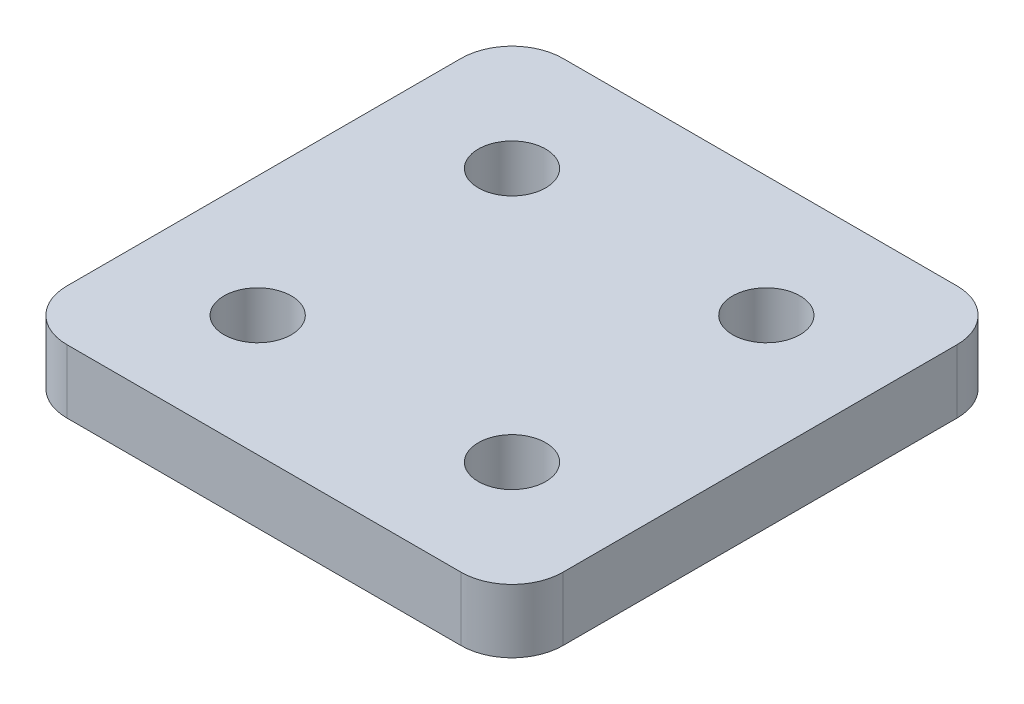
SolidWorks part; units mm, degrees
ref_plane "Top" through (0, 0, 0) normal (0, 0, 1) x (1, 0, 0)
ref_plane "Front" through (0, 0, 0) normal (0, 1, 0) x (1, 0, 0)
ref_plane "Right" through (0, 0, 0) normal (1, 0, 0) x (0, 0, -1)
sketch "2 Hole Profile Sketch" [suppressed] plane through (0, 0, 0) normal (0, 1, 0) x (1, 0, 0)
  line L0 (0, -10) -> (0, 10) construction
  line L1 (-16.5, -9.5) -> (16.5, -9.5)
  line L2 (-19.5, -6.5) -> (-19.5, 6.5)
  line L3 (-16.5, 9.5) -> (16.5, 9.5)
  line L4 (19.5, -6.5) -> (19.5, 6.5)
  line L5 (-20, -10) -> (20, -10) construction
  line L6 (-20, -10) -> (-20, 10) construction
  line L7 (-20, 10) -> (20, 10) construction
  line L8 (20, -10) -> (20, 10) construction
  arc A0 (-16.5, -9.5) -> (-19.5, -6.5) centre (-16.5, -6.5) cw
  arc A1 (-16.5, 9.5) -> (-19.5, 6.5) centre (-16.5, 6.5) ccw
  arc A2 (19.5, 6.5) -> (16.5, 9.5) centre (16.5, 6.5) ccw
  arc A3 (16.5, -9.5) -> (19.5, -6.5) centre (16.5, -6.5) ccw
  circle A4 centre (-10, 0) radius 2.65
  circle A5 centre (10, 0) radius 2.65
  point P24 (0, 0)
  dimension "D2" = 0.5
  dimension "D3" = 0.5
  dimension "D4" = 0.5
  dimension "D7" = 10
  dimension "D1" = 3
  dimension "D5" = 0.5
  dimension "D6" = 20
  dimension "D9" = 10
  dimension "D12" = 20
  dimension "D8" = 5.3
  dimension "D11" = 20
extrude "2 Hole Profile" [suppressed] add sketch "2 Hole Profile Sketch" along normal blind 5
sketch "3 Hole Profile Sketch" [suppressed] plane through (0, 0, 0) normal (0, 1, 0) x (1, 0, 0)
  line L0 (0, -10) -> (0, 10) construction
  line L1 (-16.5, -9.5) -> (36.5, -9.5)
  line L2 (-19.5, -6.5) -> (-19.5, 6.5)
  line L3 (-16.5, 9.5) -> (36.5, 9.5)
  line L4 (39.5, -6.5) -> (39.5, 6.5)
  line L5 (-20, -10) -> (40, -10) construction
  line L6 (-20, -10) -> (-20, 10) construction
  line L7 (-20, 10) -> (40, 10) construction
  line L8 (40, -10) -> (40, 10) construction
  arc A0 (-16.5, -9.5) -> (-19.5, -6.5) centre (-16.5, -6.5) cw
  arc A1 (-16.5, 9.5) -> (-19.5, 6.5) centre (-16.5, 6.5) ccw
  arc A2 (39.5, 6.5) -> (36.5, 9.5) centre (36.5, 6.5) ccw
  arc A3 (36.5, -9.5) -> (39.5, -6.5) centre (36.5, -6.5) ccw
  circle A4 centre (-10, 0) radius 2.65
  circle A5 centre (10, 0) radius 2.65
  circle A6 centre (30, 0) radius 2.65
  point P29 (0, 0)
  dimension "D2" = 0.5
  dimension "D3" = 0.5
  dimension "D4" = 0.5
  dimension "D10" = 20
  dimension "D7" = 10
  dimension "D1" = 3
  dimension "D8" = 5.3
  dimension "D5" = 0.5
  dimension "D6" = 20
  dimension "D9" = 10
  dimension "D11" = 40
  dimension "D12" = 20
extrude "3 Hole Thickness Extrude" [suppressed] add sketch "3 Hole Profile Sketch" along normal blind 5
sketch "4 Hole Profile Sketch" plane through (0, 0, 0) normal (0, 1, 0) x (1, 0, 0)
  line L1 (-15.5, -19.5) -> (15.5, -19.5)
  line L2 (-19.5, -15.5) -> (-19.5, 15.5)
  line L3 (-15.5, 19.5) -> (15.5, 19.5)
  line L4 (19.5, -15.5) -> (19.5, 15.5)
  line L5 (0, 19.5) -> (0, -19.5) construction
  line L6 (-19.5, 0) -> (19.5, 0) construction
  line L7 (-20, 20) -> (20, 20) construction
  line L8 (-20, 20) -> (-20, -20) construction
  line L9 (-20, -20) -> (20, -20) construction
  line L10 (20, 20) -> (20, -20) construction
  line L11 (-20, 20) -> (20, -20) construction
  line L12 (-20, -20) -> (20, 20) construction
  circle A0 centre (10, -10) radius 2.65
  circle A1 centre (10, 10) radius 2.65
  circle A2 centre (-10, -10) radius 2.65
  circle A3 centre (-10, 10) radius 2.65
  arc A4 (-19.5, -15.5) -> (-15.5, -19.5) centre (-15.5, -15.5) ccw
  arc A5 (19.5, -15.5) -> (15.5, -19.5) centre (15.5, -15.5) cw
  arc A6 (15.5, 19.5) -> (19.5, 15.5) centre (15.5, 15.5) cw
  arc A7 (-19.5, 15.5) -> (-15.5, 19.5) centre (-15.5, 15.5) cw
  point P14 (0, 0)
  point P22 (-25, -26)
  point P144 (0, 0)
  dimension "Corner Radius" = 4
  dimension "D9" = 5.3
  dimension "D5" = 10
  dimension "D6" = 10
  dimension "D7" = 10
  dimension "D1" = 40
  dimension "D2" = 0.5
  dimension "D3" = 0.5
  dimension "D4" = 0.5
  dimension "D10" = 20
  dimension "D8" = 10
extrude "4 Hole Thickness Extrude" add sketch "4 Hole Profile Sketch" along normal blind 5
sketch "6 Hole Extension Sketch" plane through (0, 0, 0) normal (0, 1, 0) x (1, 0, 0)
  line L0 (39.5, -15.5) -> (39.5, 15.5)
  line L1 (-20, -19.5) -> (15.5, -19.5) construction
  line L2 (-20, -19.5) -> (-20, 19.5) construction
  line L3 (-20, 19.5) -> (15.5, 19.5) construction
  line L4 (19.5, -15.5) -> (19.5, 15.5)
  line L5 (0, 19.5) -> (0, -19.5) construction
  line L6 (-20, 0) -> (19.5, 0) construction
  line L7 (15.5, -19.5) -> (35.5, -19.5)
  line L8 (15.5, 19.5) -> (35.5, 19.5)
  arc A8 (39.5, -15.5) -> (35.5, -19.5) centre (35.5, -15.5) cw
  arc A9 (35.5, 19.5) -> (39.5, 15.5) centre (35.5, 15.5) cw
  arc A10 (19.5, -15.5) -> (15.5, -19.5) centre (15.5, -15.5) cw
  arc A11 (19.5, 15.5) -> (15.5, 19.5) centre (15.5, 15.5) ccw
  circle A12 centre (30, -10) radius 2.65
  circle A13 centre (30, 10) radius 2.65
  point P18 (-22.5, -23)
  point P27 (0, 0)
  dimension "Corner Radius" = 4
  dimension "D5" = 5.3
  dimension "D1" = 19.5
  dimension "D2" = 20
  dimension "D6" = 39
  dimension "D7" = 10
  dimension "D8" = 20
  dimension "D3" = 30
  dimension "D4" = 39.5
extrude "6 Hole Extension Extrude" [suppressed] add sketch "6 Hole Extension Sketch" along normal up to surface (5 mm away)
equation "\"M5 Close Fit Hole\"= 5.3mm"
equation "\"D9@4 Hole Profile Sketch\" = \"M5 Close Fit Hole\""
equation "\"D5@6 Hole Extension Sketch\" = \"M5 Close Fit Hole\""
equation "\"Clearance\"= 0.5mm"
equation "\"D2@4 Hole Profile Sketch\"=\"Clearance\""
equation "\"D3@4 Hole Profile Sketch\"=\"Clearance\""
equation "\"D4@4 Hole Profile Sketch\"=\"Clearance\""
equation "\"D6@6 Hole Extension Sketch\"=40-2*\"Clearance\""
equation "\"D1@6 Hole Extension Sketch\"=20-\"Clearance\""
equation "\"D2@3 Hole Profile Sketch\" = \"Clearance\""
equation "\"D3@3 Hole Profile Sketch\" = \"Clearance\""
equation "\"D4@3 Hole Profile Sketch\" = \"Clearance\""
equation "\"D5@3 Hole Profile Sketch\" = \"Clearance\""
equation "\"D8@3 Hole Profile Sketch\" = \"M5 Close Fit Hole\""
equation "\"Plate Thickness\"= 5"
equation "\"D1@4 Hole Thickness Extrude\"=\"Plate Thickness\""
equation "\"D1@3 Hole Thickness Extrude\"=\"Plate Thickness\""
equation "\"D8@2 Hole Profile Sketch\" = \"M5 Close Fit Hole\""
equation "\"D1@2 Hole Profile\" = \"Plate Thickness\""
